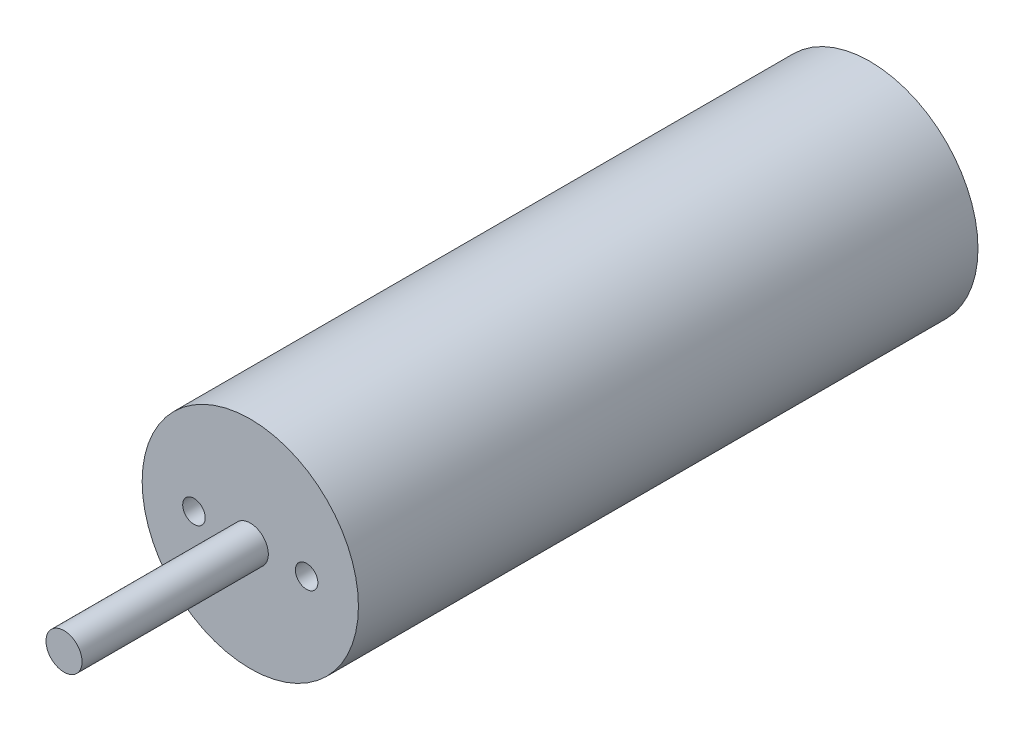
SolidWorks part; units mm, degrees
ref_plane "Front Plane" through (0, 0, 0) normal (0, 0, 1) x (1, 0, 0)
ref_plane "Top Plane" through (0, 0, 0) normal (0, 1, 0) x (1, 0, 0)
ref_plane "Right Plane" through (0, 0, 0) normal (1, 0, 0) x (0, 0, -1)
sketch "Sketch1" plane through (0, 0, 0) normal (0, 0, 1) x (1, 0, 0)
  circle A0 centre (0, 0) radius 12.192
  dimension "D1" = 24.384
extrude "Boss-Extrude1" add sketch "Sketch1" along normal blind 69.85
sketch "Sketch2" plane through (0, 0, 69.85) normal (0, 0, 1) x (1, 0, 0)
  circle A0 centre (0, 0) radius 2.032
  dimension "D1" = 4.064
extrude "Boss-Extrude2" add sketch "Sketch2" along normal blind 21
sketch "Sketch3" plane through (0, 0, 69.85) normal (0, 0, 1) x (1, 0, 0)
  line L0 (0, 0) -> (6.35, 0) construction
  line L1 (0, 0) -> (-6.35, 0) construction
  circle A0 centre (6.35, 0) radius 1.27
  circle A1 centre (-6.35, 0) radius 1.27
  dimension "D2" = 2.54
  dimension "D1" = 6.35
extrude "Cut-Extrude1" cut sketch "Sketch3" against normal blind 11.43
